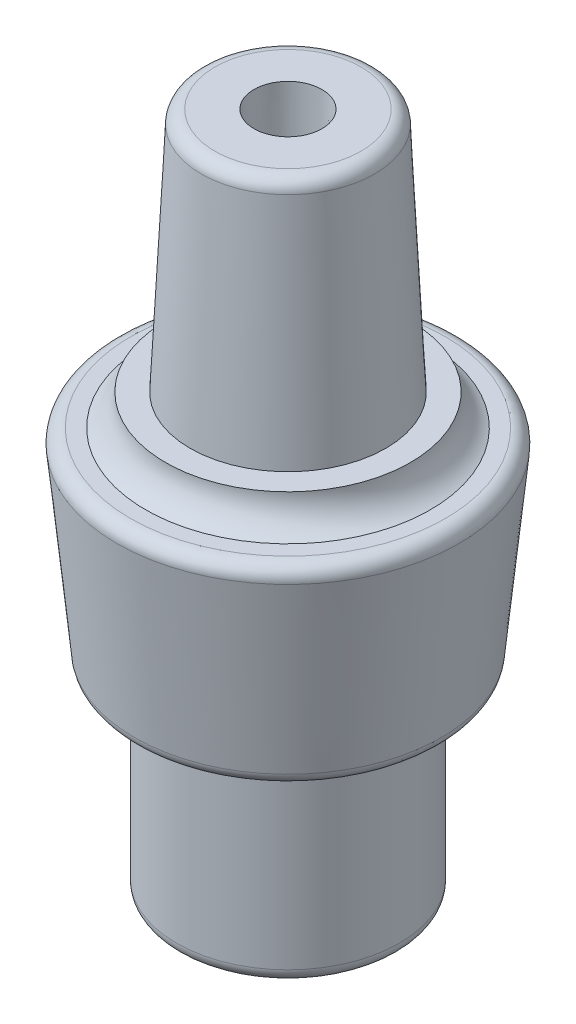
SolidWorks part; units mm, degrees
ref_plane "Front Plane" through (0, 0, 0) normal (0, 0, 1) x (1, 0, 0)
ref_plane "Top Plane" through (0, 0, 0) normal (0, 1, 0) x (1, 0, 0)
ref_plane "Right Plane" through (0, 0, 0) normal (1, 0, 0) x (0, 0, -1)
sketch "Sketch2" plane through (0, 0, 0) normal (0, 0, 1) x (1, 0, 0)
  line L0 (0, -5.25) -> (0, 5.25)
  line L2 (-0.4, -5.25) -> (-0.4, -4.75)
  line L3 (-0.4, -4.75) -> (-1.6381, -4.75)
  line L4 (-1.6381, -4.75) -> (-1.6381, -1.8052)
  line L6 (-0.4, -1.8052) -> (-0.4, -4.75)
  line L7 (-1.6381, -1.8052) -> (-2.2355, -1.8052)
  line L8 (-2.5355, 1.1948) -> (-2.2355, -1.8052)
  line L9 (-2.2355, -1.8052) -> (-1.6381, -1.8052)
  line L10 (-2.0931, 1.1948) -> (-2.5355, 1.1948) construction
  line L11 (-2.5355, 1.1948) -> (-2.0931, 1.1948)
  line L12 (-0.4, 1.1948) -> (-0.4, -1.8052)
  line L13 (-1.8, 1.65) -> (-1.4386, 1.65)
  line L14 (-0.4, 1.1948) -> (-0.4, 1.65)
  line L16 (-0.5, 5.25) -> (-0.4, 1.65)
  line L17 (-0.5, 5.25) -> (-1.2642, 5.25)
  line L18 (-1.2642, 5.25) -> (-1.4386, 1.65)
  arc A0 (-1.8, 1.65) -> (-2.0931, 1.1948) centre (-2.3, 1.65) cw
  point P4 (0, 0)
  point P19 (0, 5.25)
  dimension "D4" = 1.4
  dimension "D5" = 0.5
  dimension "D1" = 0.4
  dimension "D2" = 0.5
revolve "Revolve1" add sketch "Sketch2" angle 360 about L0
fillet "Fillet1" radius 0.2 1 edges at (0, 5.25, -1.2642)
fillet "Fillet2" radius 0.2 1 edges at (0, -4.75, -1.6381)
fillet "Fillet3" radius 0.2 2 edges at (0, -1.8052, -2.2355) (0, 1.1948, -2.5355)
